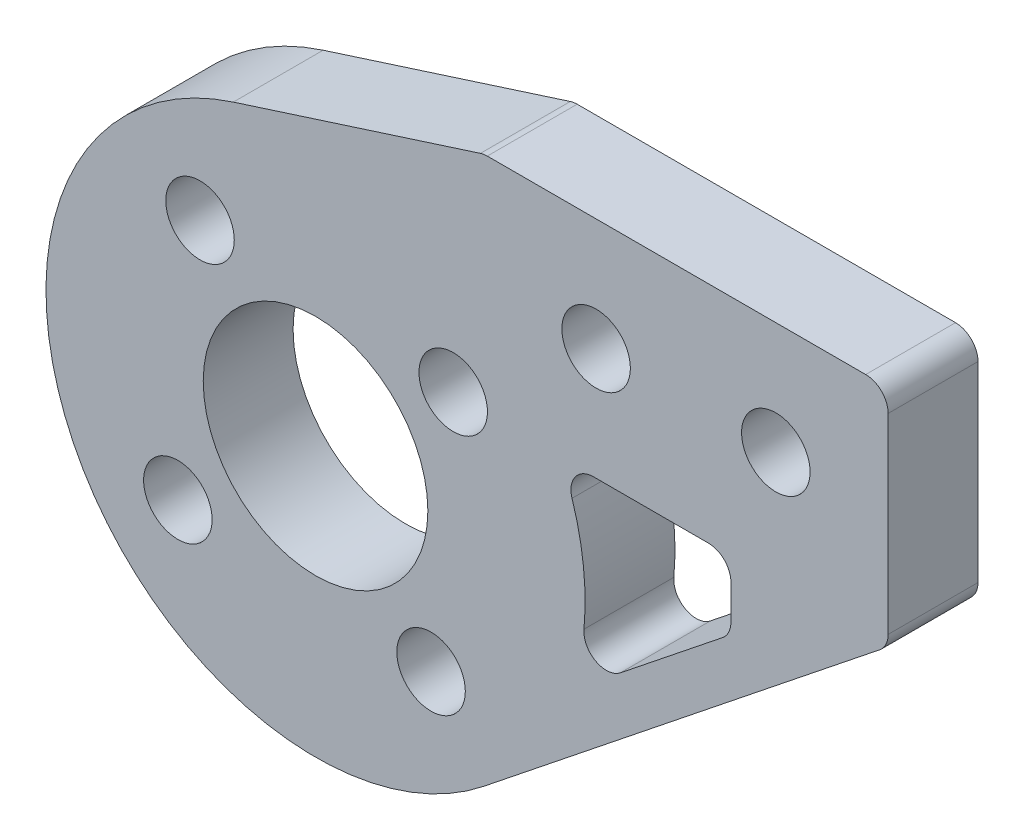
SolidWorks part; units mm, degrees
material "Thornel Mat VMA"
ref_plane "前视基准面" through (0, 0, 0) normal (0, 0, 1) x (1, 0, 0)
ref_plane "上视基准面" through (0, 0, 0) normal (0, 1, 0) x (1, 0, 0)
ref_plane "右视基准面" through (0, 0, 0) normal (1, 0, 0) x (0, 0, -1)
sketch "草图1" plane through (0, 0, 0) normal (0, 0, 1) x (1, 0, 0)
  line L0 (0, 0) -> (-50000, 0) construction
  line L1 (0, 0) -> (0, 50000) construction
  line L2 (0, 0) -> (-5.1423, 6.1284) construction
  line L3 (0, 12) -> (40.5956, 12) construction
  line L4 (25.49, 15) -> (7.49, 15)
  line L5 (25.49, 15) -> (25.49, 5)
  line L6 (25.49, 5) -> (7.4886, -9.3766)
  line L7 (7.49, 15) -> (-3.6608, 11.428)
  circle A0 centre (0, 0) radius 12
  circle A1 centre (-5.1423, 6.1284) radius 1.525
  circle A2 centre (0, 0) radius 8 construction
  circle A6 centre (12.49, 10) radius 1.525
  circle A7 centre (20.49, 10) radius 1.525
  circle A8 centre (0, 0) radius 5
  circle A9 centre (12.49, 10) radius 4 construction
  circle A10 centre (6.1284, 5.1423) radius 1.525
  circle A11 centre (5.1423, -6.1284) radius 1.525
  circle A12 centre (-6.1284, -5.1423) radius 1.525
  point P10 (6.0191, 5.2697)
  point P11 (-6.1284, -5.1423)
  point P32 (0, 0)
  dimension "D1" = 24
  dimension "D2" = 3.05
  dimension "D3" = 16
  dimension "D12" = 10
  dimension "D13" = 8
  dimension "D11" = 4
  dimension "D4" = 50
  dimension "D5" = 8
  dimension "D6" = 2
  dimension "D7" = 5
  dimension "D8" = 5
  dimension "D9" = 5
  dimension "D10" = 5
extrude "凸台-拉伸1" add sketch "草图1" along normal blind 4
sketch "草图2" plane through (0, 0, 4) normal (0, 0, 1) x (1, 0, 0)
  line L0 (5.6569, 5.6569) -> (5.6569, -5.6569) construction
  line L1 (5.6569, -5.6569) -> (20.49, 6.1895) construction
  line L2 (20.49, 6.1895) -> (20.49, 10) construction
  line L3 (20.49, 10) -> (12.49, 10) construction
  line L4 (12.49, 10) -> (5.6569, 5.6569) construction
  line L5 (25.49, 5) -> (7.4886, -9.3766) construction
  line L6 (8.6569, 4.009) -> (8.6569, -5.884)
  line L7 (8.6569, -5.884) -> (18.49, 1.9691)
  line L8 (18.49, 1.9691) -> (18.49, 5)
  line L9 (18.49, 5) -> (10.2161, 5)
  line L10 (10.2161, 5) -> (8.6569, 4.009)
  circle A0 centre (20.49, 10) radius 1.525 construction
  circle A1 centre (0, 0) radius 12
  point P21 (0, 0)
  point P22 (0, 0)
  point P23 (0, 0)
  point P24 (0, 0)
  dimension "D6" = 24
  dimension "D1" = 2
  dimension "D2" = 5
  dimension "D3" = 2
  dimension "D4" = 3
  dimension "D5" = 3
extrude "切除-拉伸1" cut sketch "草图2" against normal blind 4 contours A1 L7 L8 L9 L10
fillet "圆角1" radius 1 7 edges at (18.49, 1.9691, 2) (11.4236, -3.6744, 2) (25.49, 5, 2) (25.49, 15, 2) (7.49, 15, 2) (18.49, 5, 2) (10.9087, 5, 2)
